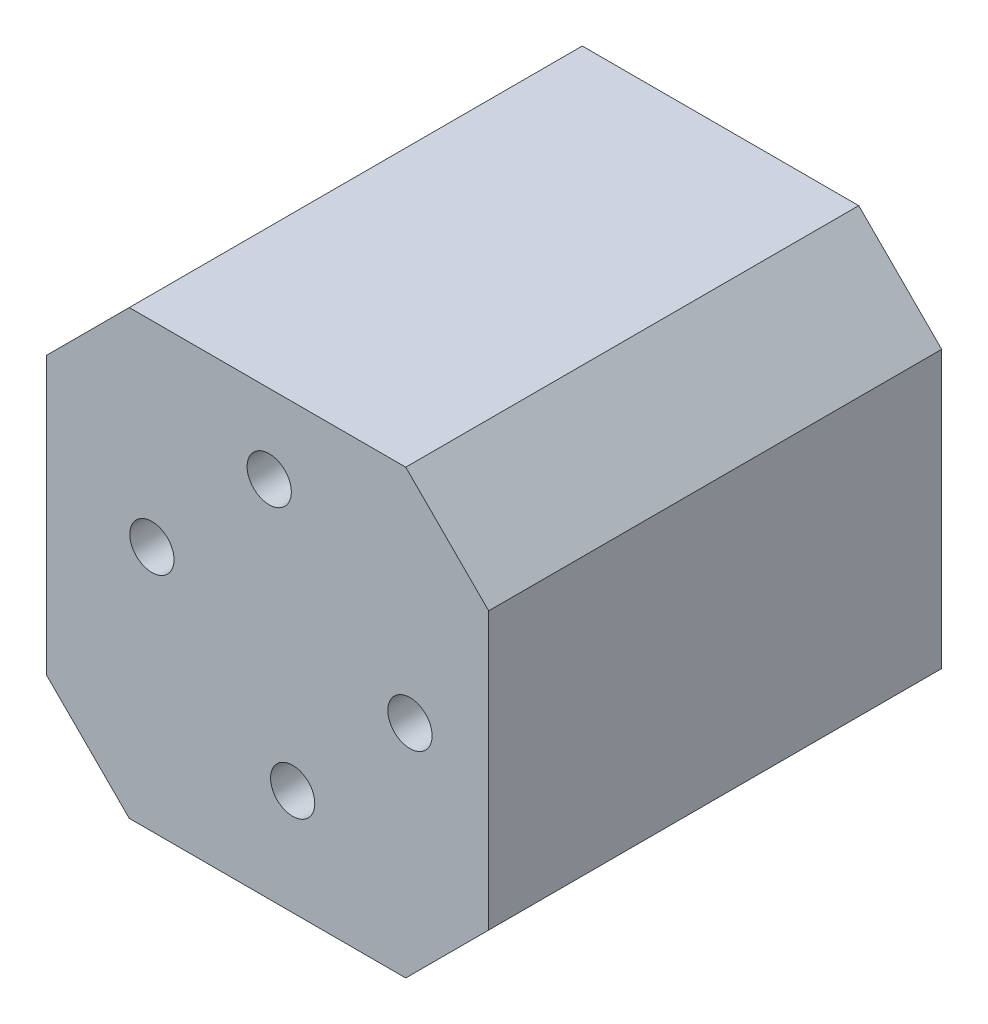
SolidWorks part; units mm, degrees
ref_plane "Front Plane" through (0, 0, 0) normal (0, 0, 1) x (1, 0, 0)
ref_plane "Top Plane" through (0, 0, 0) normal (0, 1, 0) x (1, 0, 0)
ref_plane "Right Plane" through (0, 0, 0) normal (1, 0, 0) x (0, 0, -1)
sketch "Sketch1" plane through (0, 0, 0) normal (0, 0, 1) x (1, 0, 0)
  line L0 (7.5, 40) -> (0, 32.5)
  line L1 (7.5, 0) -> (32.5, 0)
  line L2 (0, 7.5) -> (0, 32.5)
  line L3 (7.5, 40) -> (32.5, 40)
  line L4 (40, 7.5) -> (40, 32.5)
  line L5 (0, 7.5) -> (7.5, 0)
  line L6 (32.5, 40) -> (40, 32.5)
  line L7 (40, 7.5) -> (32.5, 0)
  line L8 (7.5, 0) -> (0, 0) construction
  line L9 (0, 0) -> (0, 7.5) construction
  point P0 (0, 0)
  dimension "D1" = 40
  dimension "D2" = 40
  dimension "D3" = 25
  dimension "D4" = 32.5
extrude "Boss-Extrude1" add sketch "Sketch1" along normal blind 40.96
sketch "Sketch2" plane through (0, 0, 40.96) normal (0, 0, 1) x (1, 0, 0)
  line L0 (7.5, 40) -> (0, 32.5) construction
  line L1 (20.1544, 32.8823) -> (9.5478, 22.2756) construction
  line L2 (9.5478, 22.2756) -> (22.2757, 9.5477) construction
  line L3 (22.2757, 9.5477) -> (32.8823, 20.1543) construction
  line L4 (32.8823, 20.1543) -> (20.1544, 32.8823) construction
  line L5 (32.5, 40) -> (7.5, 40) construction
  circle A0 centre (20.1544, 32.8823) radius 2
  circle A1 centre (9.5478, 22.2756) radius 2
  circle A2 centre (22.2757, 9.5477) radius 2
  circle A3 centre (32.8823, 20.1543) radius 2
  dimension "D2" = 4
  dimension "D1" = 7.1177
  dimension "D3" = 13.981
  dimension "D4" = 15
  dimension "D5" = 18
extrude "Cut-Extrude1" cut sketch "Sketch2" against normal through all
